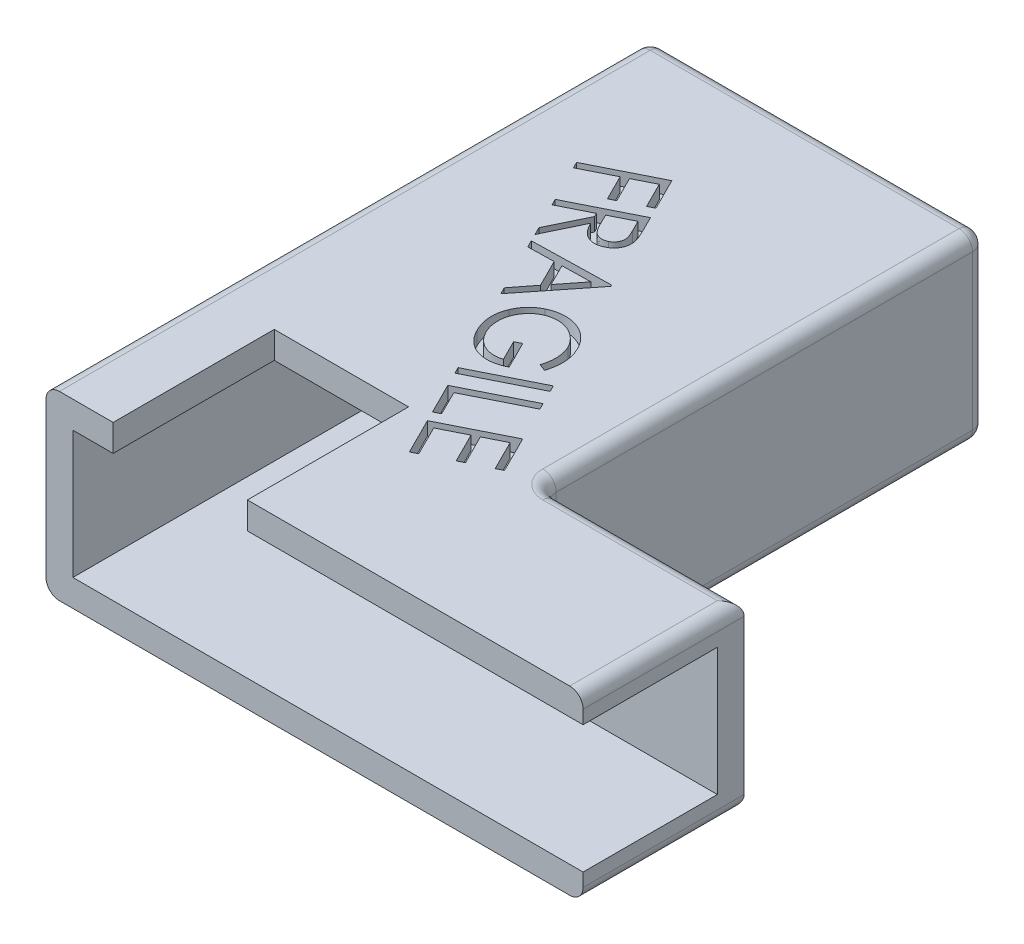
SolidWorks part; units mm, degrees
ref_plane "Front Plane" through (0, 0, 0) normal (0, 0, 1) x (1, 0, 0)
ref_plane "Top Plane" through (0, 0, 0) normal (0, 1, 0) x (1, 0, 0)
ref_plane "Right Plane" through (0, 0, 0) normal (1, 0, 0) x (0, 0, -1)
sketch "Sketch1" plane through (0, 0, 0) normal (0, 1, 0) x (1, 0, 0)
  line L0 (0, 0) -> (0, 45)
  line L5 (0, 45) -> (25, 45)
  line L6 (25, 45) -> (25, 12)
  line L7 (25, 12) -> (40, 12)
  line L8 (40, 12) -> (40, 0)
  line L9 (40, 0) -> (0, 0)
  dimension "D1" = 45
  dimension "D2" = 12
  dimension "D3" = 25
  dimension "D4" = 15
extrude "Boss-Extrude1" add sketch "Sketch1" along normal blind 6.75
sketch "Sketch4" plane through (0, 6.75, 0) normal (0, 1, 0) x (1, 0, 0)
  line L0 (2, 0) -> (2, 43)
  line L1 (0, 0) -> (40, 0) construction
  line L2 (2, 43) -> (23, 43)
  line L3 (23, 43) -> (23, 10)
  line L4 (23, 10) -> (40, 10)
  line L6 (40, 0) -> (2, 0)
  line L7 (0, 45) -> (0, 0) construction
  line L8 (25, 45) -> (0, 45) construction
  line L9 (25, 12) -> (25, 45) construction
  line L10 (40, 12) -> (25, 12) construction
  line L13 (40, 10) -> (40, 0)
  line L14 (40, 0) -> (40, 12) construction
  dimension "D1" = 2
  dimension "D2" = 2
  dimension "D3" = 2
  dimension "D4" = 2
extrude "Cut-Extrude3" cut sketch "Sketch4" against normal blind 4.75
mirror "Mirror2" about plane through (0, 6.75, 0) normal (0, -1, 0) of bodies 104
sketch "Sketch5" plane through (0, 13.5, 0) normal (0, 1, 0) x (1, 0, 0)
  line L0 (0, 45) -> (22.5, 0) construction
  line L1 (0, 0) -> (40, 0) construction
  line L4 (0, 45) -> (0, 0) construction
  text T0 " FRAGILE" font "Century Gothic" height in points 20
  dimension "D1" = 22.5
extrude "Cut-Extrude4" cut sketch "Sketch5" against normal blind 1
fillet "Fillet2" radius 1 13 edges at (25, 0, -28.5) (40, 0, -6) (40, 13.5, -6) (32.5, 13.5, -12) (32.5, 0, -12) (25, 6.75, -12) (0, 0, -22.5) (0, 13.5, -22.5) (0, 6.75, -45) (12.5, 0, -45) (25, 6.75, -45) (25, 13.5, -28.5) (12.5, 13.5, -45)
sketch "Sketch7" plane through (0, 13.5, 0) normal (0, 1, 0) x (1, 0, 0)
  line L0 (1, 0) -> (39, 0) construction
  line L1 (5, 0) -> (15, 0)
  line L2 (5, 0) -> (5, 12)
  line L3 (5, 12) -> (15, 12)
  line L4 (15, 0) -> (15, 12)
  line L5 (5, 0) -> (15, 12) construction
  line L6 (5, 12) -> (15, 0) construction
  line L7 (0, 0) -> (0, 44) construction
  point P4 (10, 6)
  dimension "D1" = 5
  dimension "D2" = 12
  dimension "D3" = 10
extrude "Cut-Extrude6" cut sketch "Sketch7" against normal up to surface (2 mm away) up to face at (21.6667, 11.5, -17.6667)
